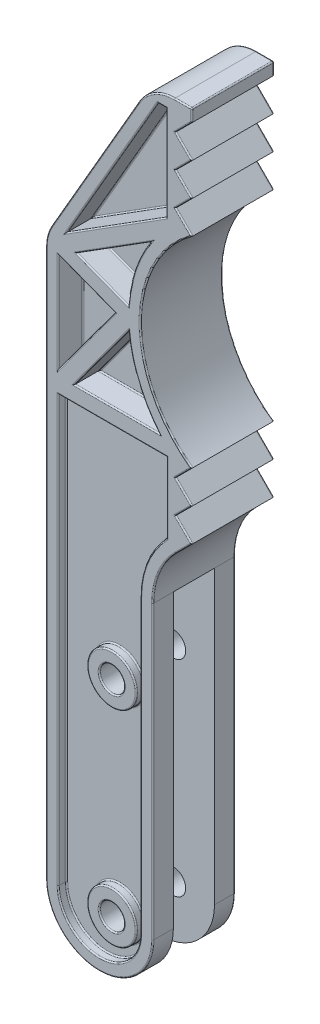
SolidWorks part; units mm, degrees
ref_plane "前视基准面" through (0, 0, 0) normal (0, 0, 1) x (1, 0, 0)
ref_plane "上视基准面" through (0, 0, 0) normal (0, 1, 0) x (1, 0, 0)
ref_plane "右视基准面" through (0, 0, 0) normal (1, 0, 0) x (0, 0, -1)
sketch "草图1" plane through (0, 0, 0) normal (0, 0, 1) x (1, 0, 0)
  line L0 (0, 0) -> (0, 90) construction
  line L1 (0, 90) -> (-5, 90) construction
  line L2 (-5, 90) -> (-17.75, 67.9164) construction
  line L3 (-17.75, 67.9164) -> (-17.75, 0) construction
  line L4 (-17.75, 0) -> (0, 0) construction
  line L5 (0, 90) -> (0, 75) construction
  line L6 (0, 90) -> (-2, 90) construction
  line L7 (0, 75) -> (-2, 75) construction
  line L8 (-2, 90) -> (-2, 75) construction
  line L9 (0, 88.5) -> (-2, 86.5)
  line L10 (-2, 86.5) -> (0, 84.5)
  line L11 (0, 84.5) -> (-2, 82.5)
  line L12 (-2, 82.5) -> (0, 80.5)
  line L13 (0, 80.5) -> (-2, 78.5)
  line L14 (-2, 78.5) -> (0, 76.5)
  line L15 (0, 64.3) -> (-17.75, 64.3) construction
  line L16 (-5, 90) -> (-17.75, 67.9164)
  line L17 (-2, 50.1) -> (0, 52.1)
  line L18 (0, 48.1) -> (-2, 50.1)
  line L19 (-2, 46.1) -> (0, 48.1)
  line L20 (0, 44.1) -> (-2, 46.1)
  line L21 (-2, 42.1) -> (0, 44.1)
  line L22 (0, 88.5) -> (0, 90)
  line L23 (0, 90) -> (-5, 90)
  line L24 (-17.75, 67.9164) -> (-17.75, 0)
  line L25 (-4.75, 0) -> (-4.75, 35.4609)
  line L26 (-9.75, 0) -> (-9.75, 25) construction
  arc A0 (0, 76.5) -> (0, 52.1) centre (8.727, 64.3) ccw
  arc A1 (-17.75, 0) -> (-4.75, 0) centre (-11.25, 0) ccw
  arc A2 (-4.75, 35.4609) -> (-2, 42.1) centre (4.6391, 35.4609) cw
  circle A3 centre (-9.75, 0) radius 1.5
  circle A4 centre (-9.75, 25) radius 1.5
  dimension "D11" = 15
  dimension "D12" = 6.5
  dimension "D13" = 3
  dimension "D1" = 90
  dimension "D2" = 30
  dimension "D3" = 5
  dimension "D4" = 17.75
  dimension "D5" = 15
  dimension "D6" = 2
  dimension "D7" = 1.5
  dimension "D8" = 3.5
  dimension "D10" = 24.2
  dimension "D14" = 5
  dimension "D15" = 25
  dimension "D9" = 3
extrude "凸台-拉伸1" add sketch "草图1" along normal mid plane 10 from offset 0
sketch "草图2" plane through (0, 0, 0) normal (0, 0, 1) x (1, 0, 0)
  line L0 (-15, -8.4108) -> (-15, 23.5892)
  line L1 (-4.75, 0) -> (-4.75, 35.4609) construction
  line L2 (-15, -8.4108) -> (-4.75, -8.4108)
  line L3 (-4.75, -8.4108) -> (-4.75, 35.4609)
  arc A0 (-15, 23.5892) -> (-4.75, 35.4609) centre (-3, 23.5892) cw
  dimension "D2" = 12
  dimension "D1" = 10.25
  dimension "D3" = 32
extrude "切除-拉伸1" cut sketch "草图2" against normal mid plane 5
sketch "草图3" plane through (0, 0, 5) normal (0, 0, 1) x (1, 0, 0)
  line L32 (-3.1276, 88.5) -> (-3.1089, 75.7962)
  line L33 (-3.0749, 52.7689) -> (-3.0607, 43.1607)
  line L48 (-2.1213, 88.5) -> (-4.134, 88.5)
  line L49 (-4.134, 88.5) -> (-16.25, 67.5144)
  line L50 (-16.25, 67.5144) -> (-16.25, 0)
  line L51 (-6.25, 0) -> (-6.25, 35.4609)
  line L52 (-3.0607, 43.1607) -> (-2.1213, 44.1)
  line L53 (-2.1213, 44.1) -> (-4.1213, 46.1)
  line L54 (-4.1213, 46.1) -> (-2.1213, 48.1)
  line L55 (-2.1213, 48.1) -> (-4.1213, 50.1)
  line L56 (-4.1213, 50.1) -> (-2.2448, 51.9765)
  line L57 (-2.2448, 76.6235) -> (-4.1213, 78.5)
  line L58 (-4.1213, 78.5) -> (-2.1213, 80.5)
  line L59 (-2.1213, 80.5) -> (-4.1213, 82.5)
  line L60 (-4.1213, 82.5) -> (-2.1213, 84.5)
  line L61 (-2.1213, 84.5) -> (-4.1213, 86.5)
  line L62 (-4.1213, 86.5) -> (-2.1213, 88.5)
  line L63 (-3.1276, 88.5) -> (-4.134, 88.5)
  line L64 (-4.134, 88.5) -> (-16.25, 67.5144)
  line L65 (-16.25, 67.5144) -> (-16.25, 0)
  line L66 (-6.25, 0) -> (-6.25, 35.4609)
  line L67 (-3.0607, 43.1607) -> (-2.1213, 44.1) construction
  line L68 (-2.1213, 44.1) -> (-4.1213, 46.1) construction
  line L69 (-4.1213, 46.1) -> (-2.1213, 48.1) construction
  line L70 (-2.1213, 48.1) -> (-4.1213, 50.1) construction
  line L71 (-4.1213, 50.1) -> (-2.2448, 51.9765) construction
  line L72 (-2.2448, 76.6235) -> (-4.1213, 78.5) construction
  line L73 (-4.1213, 78.5) -> (-2.1213, 80.5) construction
  line L74 (-2.1213, 80.5) -> (-4.1213, 82.5) construction
  line L75 (-4.1213, 82.5) -> (-2.1213, 84.5) construction
  line L76 (-2.1213, 84.5) -> (-4.1213, 86.5) construction
  line L77 (-4.1213, 86.5) -> (-2.1213, 88.5) construction
  arc A9 (-16.25, 0) -> (-6.25, 0) centre (-11.25, 0) ccw
  arc A10 (-3.0607, 43.1607) -> (-6.25, 35.4609) centre (4.6391, 35.4609) ccw
  arc A11 (-2.2448, 76.6235) -> (-2.2448, 51.9765) centre (8.727, 64.3) ccw
  arc A12 (-16.25, 0) -> (-6.25, 0) centre (-11.25, 0) ccw
  arc A13 (-3.0607, 43.1607) -> (-6.25, 35.4609) centre (4.6391, 35.4609) ccw
  arc A14 (-3.1089, 75.7962) -> (-3.0749, 52.7689) centre (8.727, 64.3) ccw
  circle M19 centre (-9.75, 25) radius 1.5
  circle M39 centre (-9.75, 0) radius 1.5
  dimension "D2" = 1.0063
  dimension "D1" = 1.5
extrude "切除-拉伸2" cut sketch "草图3" against normal blind 1 contours A14 L32 L63 L64 L65 A12 L66 A13 M39 M19
sketch "草图4" plane through (0, 0, 4) normal (0, 0, 1) x (1, 0, 0)
  circle A0 centre (-9.75, 25) radius 1.5 construction
  circle A1 centre (-9.75, 25) radius 1.5
  circle A2 centre (-9.75, 0) radius 1.5 construction
  circle A3 centre (-9.75, 0) radius 1.5
extrude "拉伸-薄壁2" add sketch "草图4" along normal blind 1 thin
sketch "草图5" plane through (0, 0, 4) normal (0, 0, 1) x (1, 0, 0)
  line L0 (-3.0749, 52.7689) -> (-16.25, 52.7689)
  line L6 (-3.1089, 75.7962) -> (-3.1276, 88.5)
  line L7 (-3.1276, 88.5) -> (-4.134, 88.5)
  line L8 (-4.134, 88.5) -> (-16.25, 67.5144)
  line L9 (-16.25, 67.5144) -> (-16.25, 0)
  line L10 (-6.25, 0) -> (-6.25, 35.4609)
  line L11 (-3.0607, 43.1607) -> (-3.0749, 52.7689)
  line L12 (-3.1089, 75.7962) -> (-3.1276, 88.5)
  line L13 (-3.1276, 88.5) -> (-4.134, 88.5)
  line L14 (-4.134, 88.5) -> (-16.25, 67.5144)
  line L15 (-16.25, 67.5144) -> (-16.25, 0)
  line L16 (-6.25, 0) -> (-6.25, 35.4609)
  line L17 (-3.0607, 43.1607) -> (-3.0749, 52.7689) construction
  arc A3 (-3.1089, 75.7962) -> (-3.0749, 52.7689) centre (8.727, 64.3) ccw
  arc A4 (-16.25, 0) -> (-6.25, 0) centre (-11.25, 0) ccw
  arc A5 (-3.0607, 43.1607) -> (-6.25, 35.4609) centre (4.6391, 35.4609) ccw
  arc A6 (-3.1089, 75.7962) -> (-3.0749, 52.7689) centre (8.727, 64.3) ccw
  arc A7 (-16.25, 0) -> (-6.25, 0) centre (-11.25, 0) ccw
  arc A8 (-3.0607, 43.1607) -> (-6.25, 35.4609) centre (4.6391, 35.4609) ccw construction
  arc M11 (-3.0749, 52.7689) -> (-3.1089, 75.7962) centre (8.727, 64.3) cw
  line M12 (-3.1089, 75.7962) -> (-3.1276, 88.5)
  line M13 (-3.1276, 88.5) -> (-4.134, 88.5)
  line M14 (-4.134, 88.5) -> (-16.25, 67.5144)
  line M15 (-16.25, 67.5144) -> (-16.25, 0)
  dimension "D1" = 0
extrude "切除-拉伸3" cut sketch "草图5" against normal blind 2 contours L0 M11 M12 M13 M14 M15
sketch "草图6" plane through (0, 0, 5) normal (0, 0, 1) x (1, 0, 0)
  line L0 (-3.0749, 52.7689) -> (-16.25, 52.7689)
  line L1 (-16.25, 52.7689) -> (-7.773, 64.2756)
  line L2 (-7.773, 64.2756) -> (-16.25, 67.5144)
  line L3 (-16.25, 67.5144) -> (-3.1089, 75.7962)
  arc A0 (-3.1089, 75.7962) -> (-3.0749, 52.7689) centre (8.727, 64.3) ccw construction
extrude "拉伸-薄壁3" add sketch "草图6" against normal up to body separate body thin contours L0 L1 L2 L3 thin type mid plane wall 2
sketch "草图7" plane through (0, 0, 5) normal (0, 0, 1) x (1, 0, 0)
  line L0 (-3.642, 76.6422) -> (-3.1089, 75.7962) construction
  line L1 (-3.642, 76.6422) -> (-3.1089, 75.7962)
  line L2 (-3.642, 76.6422) -> (-3.1106, 76.9771)
  line L3 (-3.1276, 88.5) -> (-3.1089, 75.7962) construction
  line L4 (-3.1106, 76.9771) -> (-3.1089, 75.7962)
  line L5 (-15.1772, 69.3725) -> (-3.642, 76.6422) construction
extrude "凸台-拉伸2" add sketch "草图7" against normal up to body separate body
sketch "草图8" plane through (0, 0, 5) normal (0, 0, 1) x (1, 0, 0)
  line L0 (-3.0749, 52.7689) -> (-3.0749, 51.7689) construction
  line L1 (-3.0749, 52.7689) -> (-3.0749, 51.7689)
  line L2 (-3.0749, 51.7689) -> (-3.0734, 51.7689)
  line L3 (-3.0749, 52.7689) -> (-3.0607, 43.1607) construction
  line L4 (-3.0734, 51.7689) -> (-3.0749, 52.7689)
extrude "凸台-拉伸3" add sketch "草图8" along direction (0, 0, 1) on the side against the normal up to next (1 mm away)
mirror "镜向1" about plane through (0, 0, 0) normal (0, 0, 1) of "凸台-拉伸3", "切除-拉伸1", "切除-拉伸2", "拉伸-薄壁2", "切除-拉伸3", "拉伸-薄壁3", "凸台-拉伸2"
fillet "圆角8" radius 5 2 edges at (-5, 90, 0) (-17.75, 67.9164, 0)
fillet "圆角9" radius 0.15 131 edges at (-6.75, 25, 5) (-6.75, 25, 4) (-8.25, 25, 5) (-6.75, 0, 5) (-6.75, 0, 4) (-8.25, 0, 5) (-9.6556, 78.9363, 2) (-3.6308, 88.5, 2) (-6.5037, 57.9537, 2) (-6.9177, 69.5434, 2) (-16.25, 60.4494, 2) (-16.25, 60.4494, 5) (-16.25, 25.8844, 5) (-16.25, 25.8844, 4) (-6.9177, 69.5434, 5) (-6.5037, 57.9537, 5) (-9.5312, 70.5667, 2) (-10.8827, 66.5343, 2) (-10.983, 58.2323, 2) (-9.1232, 53.7689, 2) (-9.6617, 51.7689, 4) (-11.25, -6.5, 5) (-9.6617, 51.7689, 5) (-12.8038, 59.1327, 2) (-12.8038, 59.1327, 5) (-12.8038, 65.1272, 2) (-12.8038, 65.1272, 5) (-9.1439, 73.1748, 5) (-9.1439, 73.1748, 2) (-9.1232, 53.7689, 5) (-10.983, 58.2323, 5) (-10.8827, 66.5343, 5) (-9.5312, 70.5667, 5) (0, 89.25, -5) (-1, 87.5, -5) (-1, 85.5, -5) (-1, 83.5, -5) (-1, 81.5, -5) (-3.1191, 82.7386, 2) (-1, 79.5, -5) (-1, 77.5, -5) (-4.75, 17.7305, 5) (-6.273, 64.3, -5) (-1, 51.1, -5) (-3.067, 47.4648, 5) (-3.067, 47.4648, 4) (-1, 49.1, -5) (-1, 47.1, -5) (-1, 45.1, -5) (-1, 43.1, -5) (-4.0353, 39.054, -5) (-4.75, 17.7305, -5) (-11.25, -6.5, -5) (-4.0353, 39.054, 5) (-3.6308, 88.5, -5) (-9.6556, 78.9363, -5) (-11.25, -5, -5) (-6.25, 17.7305, -5) (-5.4211, 39.628, -4) (-11.25, -5, -4) (-6.25, 17.7305, -4) (-5.4211, 39.628, -5) (-1.0566, 90, -5) (-3.1191, 82.7386, -5) (-12.75, 25, -4) (-6.75, 25, -5) (-8.25, 25, -5) (-12.75, 0, -4) (-6.75, 0, -5) (-8.25, 0, -5) (-3.6308, 88.5, -2) (-9.6556, 78.9363, -2) (-1, 43.1, 5) (-16.25, 60.4494, -2) (-6.5037, 57.9537, -2) (-6.9177, 69.5434, -2) (-16.25, 25.8844, -4) (-16.25, 60.4494, -5) (-16.25, 25.8844, -5) (0, 90, 0) (-6.9177, 69.5434, -5) (-6.5037, 57.9537, -5) (-9.1439, 73.1748, -2) (-12.8038, 65.1272, -2) (-12.8038, 59.1327, -2) (-9.6617, 51.7689, -4) (-9.1232, 53.7689, -2) (-9.1232, 53.7689, -5) (-10.983, 58.2323, -2) (-10.983, 58.2323, -5) (-10.8827, 66.5343, -2) (-10.8827, 66.5343, -5) (-9.5312, 70.5667, -2) (-1, 45.1, 5) (-9.5312, 70.5667, -5) (-9.6617, 51.7689, -5) (-12.8038, 59.1327, -5) (-12.8038, 65.1272, -5) (-9.1439, 73.1748, -5) (-3.1191, 82.7386, -2) (-3.067, 47.4648, -4) (-1, 47.1, 5) (-3.067, 47.4648, -5) (-11.7618, 78.2883, -5) (-11.7618, 78.2883, 5) (-17.75, 33.2883, -5) (-17.5796, 67.8707, -5) (-4.6132, 89.3301, -5) (-17.75, 33.2883, 5) (-17.5796, 67.8707, 5) (-4.6132, 89.3301, 5) (-1, 49.1, 5) (-1, 51.1, 5) (-6.273, 64.3, 5) (-1.0566, 90, 5) (-1, 77.5, 5) (-1, 79.5, 5) (-1, 81.5, 5) (-1, 83.5, 5) (-1, 85.5, 5) (-1, 87.5, 5) (0, 89.25, 5) (-5.4211, 39.628, 5) (-6.25, 17.7305, 4) (-11.25, -5, 4) (-3.1191, 82.7386, 5) (-5.4211, 39.628, 4) (-3.6308, 88.5, 5) (-9.6556, 78.9363, 5) (-11.25, -5, 5) (-6.25, 17.7305, 5)
